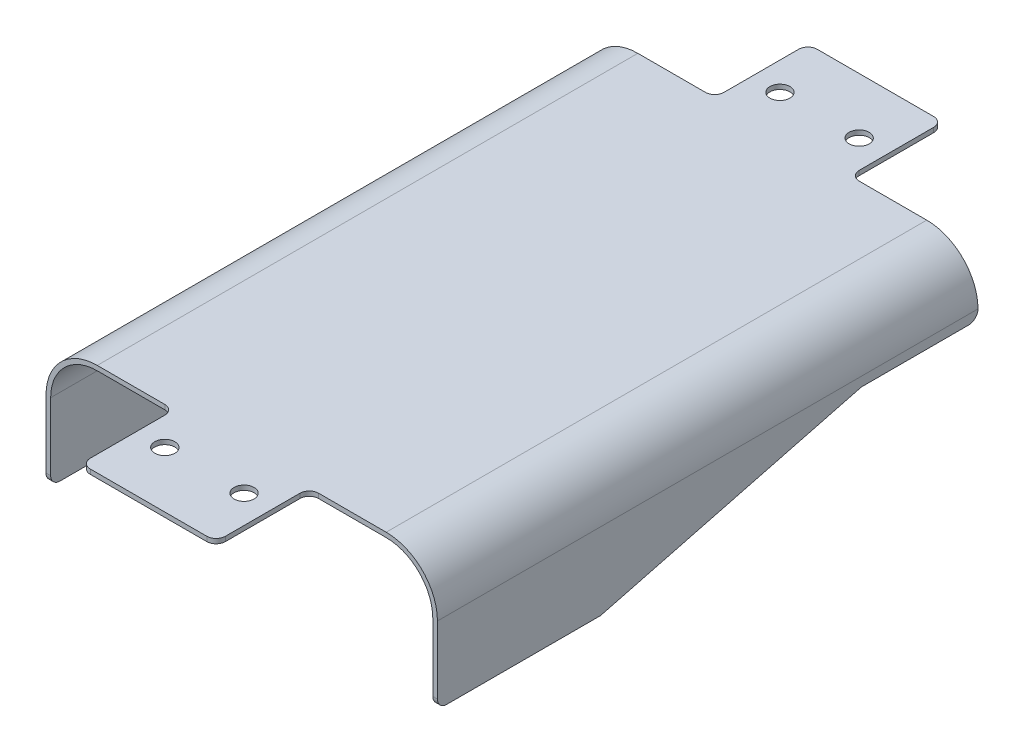
SolidWorks part; units mm, degrees
ref_plane "Front Plane" through (0, 0, 0) normal (0, 0, 1) x (1, 0, 0)
ref_plane "Top Plane" through (0, 0, 0) normal (0, 1, 0) x (1, 0, 0)
ref_plane "Right Plane" through (0, 0, 0) normal (1, 0, 0) x (0, 0, -1)
sketch "Sketch1" plane through (0, 0, 0) normal (0, 0, 1) x (1, 0, 0)
  line L0 (31, 29.5) -> (-31, 29.5)
  line L1 (-42, 18.5) -> (-42, -18.5)
  line L2 (-31, -29.5) -> (31, -29.5)
  line L3 (42, -18.5) -> (42, 18.5)
  line L4 (31, 27.5) -> (-31, 27.5)
  line L5 (-40, 18.5) -> (-40, -18.5)
  line L6 (-31, -27.5) -> (31, -27.5)
  line L7 (40, -18.5) -> (40, 18.5)
  line L8 (31, 27.5) -> (-31, 27.5)
  line L9 (-40, 18.5) -> (-40, -18.5)
  line L10 (-31, -27.5) -> (31, -27.5)
  line L11 (40, -18.5) -> (40, 18.5)
  line L12 (41, -18.5) -> (41, 18.5)
  line L13 (31, 28.5) -> (-31, 28.5)
  line L14 (-41, 18.5) -> (-41, -18.5)
  line L15 (-31, -28.5) -> (31, -28.5)
  arc A0 (-31, 29.5) -> (-42, 18.5) centre (-31, 18.5) ccw
  arc A1 (-42, -18.5) -> (-31, -29.5) centre (-31, -18.5) ccw
  arc A2 (31, -29.5) -> (42, -18.5) centre (31, -18.5) ccw
  arc A3 (42, 18.5) -> (31, 29.5) centre (31, 18.5) ccw
  arc A4 (40, 18.5) -> (31, 27.5) centre (31, 18.5) ccw
  arc A5 (-31, 27.5) -> (-40, 18.5) centre (-31, 18.5) ccw
  arc A6 (-40, -18.5) -> (-31, -27.5) centre (-31, -18.5) ccw
  arc A7 (31, -27.5) -> (40, -18.5) centre (31, -18.5) ccw
  arc A8 (40, 18.5) -> (31, 27.5) centre (31, 18.5) ccw
  arc A9 (-31, 27.5) -> (-40, 18.5) centre (-31, 18.5) ccw
  arc A10 (-40, -18.5) -> (-31, -27.5) centre (-31, -18.5) ccw
  arc A11 (31, -27.5) -> (40, -18.5) centre (31, -18.5) ccw
  arc A12 (31, -28.5) -> (41, -18.5) centre (31, -18.5) ccw
  arc A13 (41, 18.5) -> (31, 28.5) centre (31, 18.5) ccw
  arc A14 (-31, 28.5) -> (-41, 18.5) centre (-31, 18.5) ccw
  arc A15 (-41, -18.5) -> (-31, -28.5) centre (-31, -18.5) ccw
  dimension "D1" = 0
  dimension "D2" = 2
  dimension "D3" = 1
extrude "Boss-Extrude1" add sketch "Sketch1" against normal up to surface (116 mm away) contours L3 A3 L0 A0 L1 A1 L2 A2 A15 L14 A14 L13 A13 L12 A12 L15
sketch "Sketch2" plane through (0, 29.5, 0) normal (0, 1, 0) x (1, 0, 0)
  line L1 (-14.5, 0) -> (14.5, 0)
  line L2 (-14.5, 0) -> (-14.5, -20)
  line L3 (-14.5, -20) -> (14.5, -20)
  line L4 (14.5, 0) -> (14.5, -20)
  line L5 (-14.5, -27.5) -> (-14.5, 0) construction
  line L6 (14.5, 0) -> (14.5, -27.5) construction
  line L7 (-31, 116) -> (31, 116) construction
  line L8 (-14.5, 116) -> (14.5, 116)
  line L9 (-14.5, 116) -> (-14.5, 136)
  line L10 (-14.5, 136) -> (14.5, 136)
  line L11 (14.5, 116) -> (14.5, 136)
  line L12 (-14.5, 116) -> (-14.5, 143.5) construction
  line L13 (14.5, 143.5) -> (14.5, 116) construction
  line L14 (31, 0) -> (-31, 0) construction
  dimension "D1" = 20
  dimension "D2" = 20
extrude "Boss-Extrude2" add sketch "Sketch2" against normal blind 1
sketch "Sketch3" plane through (42, 0, 0) normal (1, 0, 0) x (0, 0, -1)
  line L0 (0, 2) -> (35, 2)
  line L2 (35, 2) -> (91, 16.5)
  line L3 (91, 16.5) -> (116, 16.5)
  line L4 (116, 18.5) -> (116, -18.5) construction
  line L5 (0, 2) -> (0, -29.5)
  line L6 (0, -29.5) -> (116, -29.5)
  line L7 (116, -29.5) -> (116, 16.5)
  line L8 (0, -18.5) -> (0, -29.5) construction
  dimension "D1" = 2
  dimension "D2" = 2
  dimension "D3" = 35
  dimension "D4" = 25
extrude "Cut-Extrude1" cut sketch "Sketch3" against normal through all
fillet "Fillet1" radius 2 12 edges at (-41.5, 16.5, -116) (-14.5, 29, -136) (-14.5, 29, -116) (14.5, 29, -116) (14.5, 29, -136) (41.5, 16.5, -116) (-14.5, 29, 20) (14.5, 29, 20) (-14.5, 29, 0) (-41.5, 2, 0) (14.5, 29, 0) (41.5, 2, 0)
sketch "Sketch4" plane through (0, 29.5, 0) normal (0, 1, 0) x (1, 0, 0)
  circle A0 centre (8.5, 124) radius 2.15 construction
  circle A1 centre (-8.5, 124) radius 2.15 construction
  circle A2 centre (8.5, -8) radius 2.15 construction
  circle A3 centre (-8.5, -8) radius 2.15 construction
  circle A4 centre (8.5, 124) radius 2.15
  circle A5 centre (-8.5, 124) radius 2.15
  circle A6 centre (8.5, -8) radius 2.15
  circle A7 centre (-8.5, -8) radius 2.15
extrude "Cut-Extrude2" cut sketch "Sketch4" against normal up to surface (1 mm away) up to face at (0, 28.5, -58)
